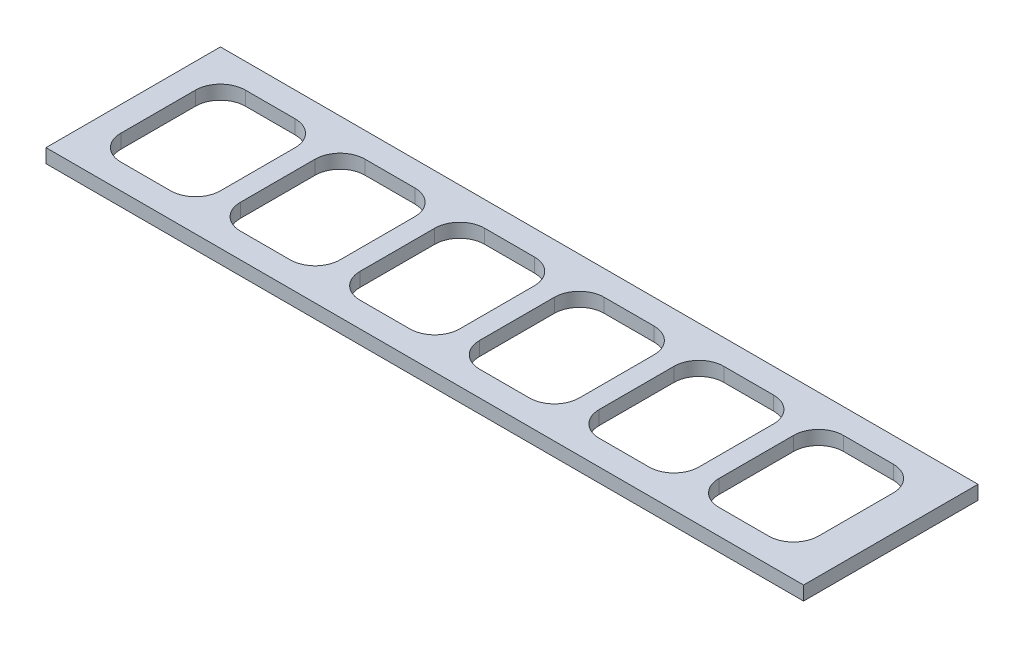
SolidWorks part; units mm, degrees
material "Balsa"
ref_plane "Front Plane" through (0, 0, 0) normal (0, 0, 1) x (1, 0, 0)
ref_plane "Top Plane" through (0, 0, 0) normal (0, 1, 0) x (1, 0, 0)
ref_plane "Right Plane" through (0, 0, 0) normal (1, 0, 0) x (0, 0, -1)
sketch "Sketch1" plane through (0, 0, 0) normal (0, 1, 0) x (1, 0, 0)
  line L0 (73.66, 63.5) -> (73.66, 25.4)
  line L1 (0, 0) -> (386.08, 0)
  line L2 (0, 0) -> (0, 88.9)
  line L3 (0, 88.9) -> (386.08, 88.9)
  line L4 (386.08, 0) -> (386.08, 88.9)
  line L5 (25.4, 76.2) -> (50.8, 76.2)
  line L6 (12.7, 63.5) -> (12.7, 25.4)
  line L7 (25.4, 12.7) -> (50.8, 12.7)
  line L8 (63.5, 63.5) -> (63.5, 25.4)
  line L9 (86.36, 76.2) -> (111.76, 76.2)
  line L10 (124.46, 63.5) -> (124.46, 25.4)
  line L11 (86.36, 12.7) -> (111.76, 12.7)
  line L12 (134.62, 63.5) -> (134.62, 25.4)
  line L13 (147.32, 76.2) -> (172.72, 76.2)
  line L14 (185.42, 63.5) -> (185.42, 25.4)
  line L15 (147.32, 12.7) -> (172.72, 12.7)
  line L16 (195.58, 63.5) -> (195.58, 25.4)
  line L17 (208.28, 76.2) -> (233.68, 76.2)
  line L18 (246.38, 63.5) -> (246.38, 25.4)
  line L19 (208.28, 12.7) -> (233.68, 12.7)
  line L20 (256.54, 63.5) -> (256.54, 25.4)
  line L21 (269.24, 76.2) -> (294.64, 76.2)
  line L22 (307.34, 63.5) -> (307.34, 25.4)
  line L23 (269.24, 12.7) -> (294.64, 12.7)
  line L24 (317.5, 63.5) -> (317.5, 25.4)
  line L25 (330.2, 76.2) -> (355.6, 76.2)
  line L26 (368.3, 63.5) -> (368.3, 25.4)
  line L27 (330.2, 12.7) -> (355.6, 12.7)
  arc A0 (12.7, 25.4) -> (25.4, 12.7) centre (25.4, 25.4) ccw
  arc A1 (50.8, 12.7) -> (63.5, 25.4) centre (50.8, 25.4) ccw
  arc A2 (50.8, 76.2) -> (63.5, 63.5) centre (50.8, 63.5) cw
  arc A3 (25.4, 76.2) -> (12.7, 63.5) centre (25.4, 63.5) ccw
  arc A4 (86.36, 76.2) -> (73.66, 63.5) centre (86.36, 63.5) ccw
  arc A5 (73.66, 25.4) -> (86.36, 12.7) centre (86.36, 25.4) ccw
  arc A6 (111.76, 76.2) -> (124.46, 63.5) centre (111.76, 63.5) cw
  arc A7 (111.76, 12.7) -> (124.46, 25.4) centre (111.76, 25.4) ccw
  arc A8 (147.32, 76.2) -> (134.62, 63.5) centre (147.32, 63.5) ccw
  arc A9 (134.62, 25.4) -> (147.32, 12.7) centre (147.32, 25.4) ccw
  arc A10 (172.72, 76.2) -> (185.42, 63.5) centre (172.72, 63.5) cw
  arc A11 (172.72, 12.7) -> (185.42, 25.4) centre (172.72, 25.4) ccw
  arc A12 (208.28, 76.2) -> (195.58, 63.5) centre (208.28, 63.5) ccw
  arc A13 (195.58, 25.4) -> (208.28, 12.7) centre (208.28, 25.4) ccw
  arc A14 (233.68, 76.2) -> (246.38, 63.5) centre (233.68, 63.5) cw
  arc A15 (233.68, 12.7) -> (246.38, 25.4) centre (233.68, 25.4) ccw
  arc A16 (269.24, 76.2) -> (256.54, 63.5) centre (269.24, 63.5) ccw
  arc A17 (256.54, 25.4) -> (269.24, 12.7) centre (269.24, 25.4) ccw
  arc A18 (294.64, 76.2) -> (307.34, 63.5) centre (294.64, 63.5) cw
  arc A19 (294.64, 12.7) -> (307.34, 25.4) centre (294.64, 25.4) ccw
  arc A20 (330.2, 76.2) -> (317.5, 63.5) centre (330.2, 63.5) ccw
  arc A21 (317.5, 25.4) -> (330.2, 12.7) centre (330.2, 25.4) ccw
  arc A22 (355.6, 76.2) -> (368.3, 63.5) centre (355.6, 63.5) cw
  arc A23 (355.6, 12.7) -> (368.3, 25.4) centre (355.6, 25.4) ccw
  dimension "D3" = 12.7
  dimension "D1" = 386.08
  dimension "D2" = 88.9
  dimension "D4" = 12.7
  dimension "D5" = 50.8
  dimension "D6" = 63.5
  dimension "D7" = 12.7
  dimension "D8" = 6
  dimension "D9" = 10.16
extrude "Boss-Extrude1" add sketch "Sketch1" along normal blind 7.112
